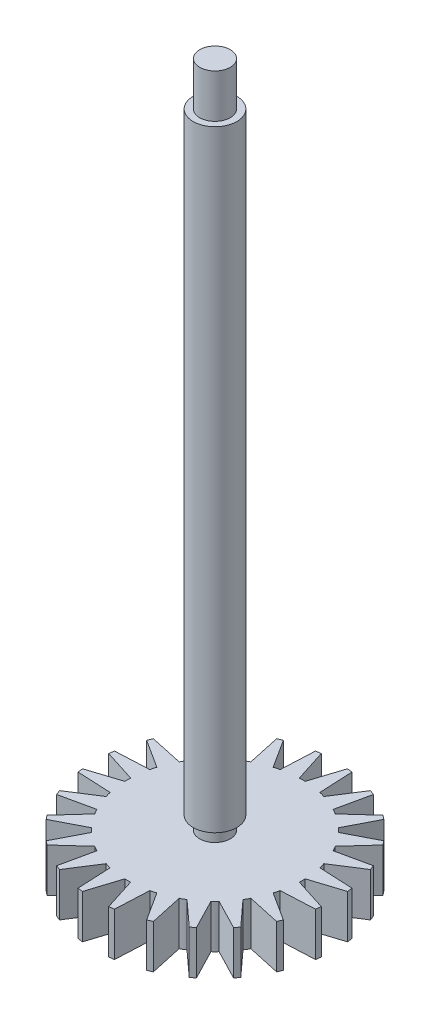
SolidWorks part; units mm, degrees
ref_plane "Front Plane" through (0, 0, 0) normal (0, 0, 1) x (1, 0, 0)
ref_plane "Top Plane" through (0, 0, 0) normal (0, 1, 0) x (1, 0, 0)
ref_plane "Right Plane" through (0, 0, 0) normal (1, 0, 0) x (0, 0, -1)
sketch "Sketch1" plane through (0, 0, 0) normal (0, 1, 0) x (1, 0, 0)
  circle A0 centre (0, 0) radius 5
  dimension "D1" = 10
extrude "centerScrew" add sketch "Sketch1" along normal blind 140
sketch "Sketch2" plane through (0, 0, 0) normal (0, -1, 0) x (1, 0, 0)
  circle A0 centre (0, 0) radius 3.5
  dimension "D1" = 7
extrude "teethWheelConnector" add sketch "Sketch2" along normal blind 17
hole_wizard "innerHole" positions "Sketch3" profile "Sketch4" hole size "Ø4.0" standard "ANSI Metric"
sketch "Sketch3" plane through (0, -17, 0) normal (0, -1, 0) x (-1, 0, 0)
  point P0 (0, 0)
sketch "Sketch4" plane through (0, -17, 0) normal (1, 0, 0) x (0, 0, -1)
  line L0 (0, 0) -> (0, 11.2017)
  line L1 (0, 11.2017) -> (2, 10)
  line L2 (2, 10) -> (2, 0)
  line L5 (2, 0) -> (0, 0)
  line L10 (0, 11.2017) -> (-2, 10) construction
  line L11 (0, -6.35) -> (0, 107.95) construction
  dimension "Hole Dia." = 4
  dimension "Hole Depth" = 10
  dimension "Drill Angle" = 118
ref_plane "centerReference" through (0, 0, 0) normal (0, -1, 0) x (-1, 0, 0)
ref_plane "teethWheelPlane" through (0, -8, 0) normal (0, -1, 0) x (-1, 0, 0)
sketch "Sketch5" plane through (0, -8, 0) normal (0, -1, 0) x (-1, 0, 0)
  circle A0 centre (0, 0) radius 27.5
  point P3 (-4.5405, 27.1226)
  dimension "D1" = 55
extrude "Boss-Extrude3" add sketch "Sketch5" along normal mid plane 10
sketch "Sketch9" plane through (0, -8, 0) normal (0, -1, 0) x (-1, 0, 0)
  line L3 (4.0139, 30.4883) -> (0.6526, 19.9572)
  line L4 (-0.6526, 19.9572) -> (-4.0139, 30.4883)
  arc A2 (4.0139, 30.4883) -> (-4.0139, 30.4883) centre (0, 15) ccw
  arc A3 (0.6526, 19.9572) -> (-0.6526, 19.9572) centre (0, 15) ccw
  point P4 (0, 31)
  point P6 (0, 20)
  point P7 (0, 0)
  point P8 (0.4146, 4.539)
  point P11 (0, 20.9156)
  point P12 (0, 0)
  point P14 (0, 0)
  point P16 (0, 0)
  point P17 (0, 0)
  dimension "D2" = 11
  dimension "D3" = 15
  dimension "D1" = 5
  dimension "D4" = 15
  dimension "D5" = 15
extrude "Cut-Extrude5" cut sketch "Sketch9" against normal mid plane 10
pattern_circular "CirPattern1" count 24 over 360 about axis through (0, 0, 0) along (0, 1, 0) of "Cut-Extrude5"
ref_plane "upperPlane" through (0, 140, 0) normal (0, 1, 0) x (1, 0, 0)
sketch "Sketch10" plane through (0, 140, 0) normal (0, 1, 0) x (1, 0, 0)
  circle A0 centre (0, 0) radius 3.5
  dimension "D1" = 7
extrude "Boss-Extrude4" add sketch "Sketch10" along normal blind 10
